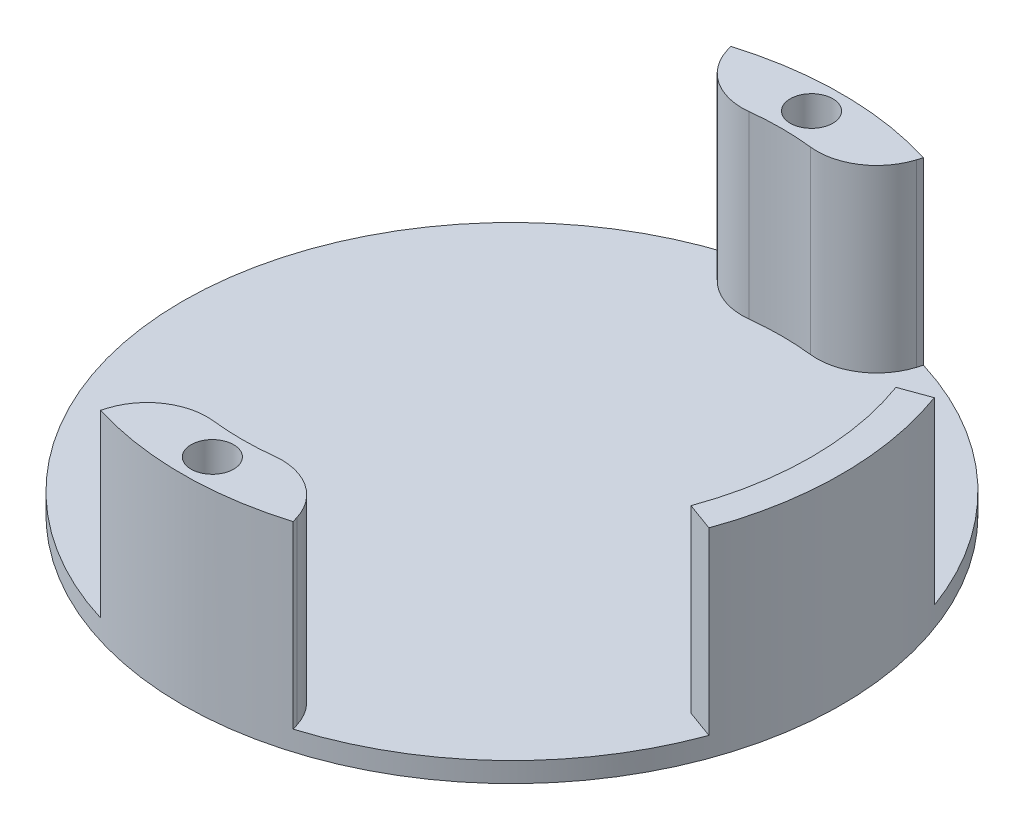
SolidWorks part; units mm, degrees
ref_plane "Front Plane" through (0, 0, 0) normal (0, 0, 1) x (1, 0, 0)
ref_plane "Top Plane" through (0, 0, 0) normal (0, 1, 0) x (1, 0, 0)
ref_plane "Right Plane" through (0, 0, 0) normal (1, 0, 0) x (0, 0, -1)
sketch "Sketch2" plane through (0, 0, 0) normal (0, 1, 0) x (1, 0, 0)
  circle A0 centre (0, 0) radius 69.85
  dimension "D1" = 139.7
extrude "Boss-Extrude1" add sketch "Sketch2" along normal blind 4.2333
sketch "Sketch3" plane through (0, 4.2333, 0) normal (0, 1, 0) x (1, 0, 0)
  line L0 (-20.4222, 66.7979) -> (-16.709, 54.6528)
  line L5 (20.4222, 66.7979) -> (16.709, 54.6528)
  line L6 (16.709, -54.6528) -> (20.4222, -66.7979)
  line L7 (-16.709, -54.6528) -> (-20.4222, -66.7979)
  arc A6 (20.4222, 66.7979) -> (-20.4222, 66.7979) centre (0, 0) ccw
  arc A7 (-16.709, -54.6528) -> (16.709, -54.6528) centre (0, 0) ccw
  arc A8 (-20.4222, -66.7979) -> (20.4222, -66.7979) centre (0, 0) ccw
  arc A9 (16.709, 54.6528) -> (-16.709, 54.6528) centre (0, 0) ccw
  circle M3 centre (0, 0) radius 69.85
  dimension "D1" = 114.3
extrude "Boss-Extrude2" add sketch "Sketch3" along normal blind 38.1 contours A7 L7 L6 M3 | A9 L5 L0 M3
fillet "Fillet3" radius 12.7 1 edges at (-16.709, 23.2833, -54.6528)
fillet "Fillet4" radius 12.7 1 edges at (16.709, 23.2833, 54.6528)
fillet "Fillet5" radius 12.7 1 edges at (-16.709, 23.2833, 54.6528)
sketch "Sketch4" plane through (0, 4.2333, 0) normal (0, 1, 0) x (1, 0, 0)
  line L0 (59.6705, 21.7183) -> (65.6375, 23.8901)
  line L1 (59.6705, -21.7183) -> (65.6375, -23.8901)
  arc A0 (65.6375, -23.8901) -> (65.6375, 23.8901) centre (0, 0) ccw
  arc A1 (59.6705, -21.7183) -> (59.6705, 21.7183) centre (0, 0) ccw
  dimension "D1" = 127
extrude "Boss-Extrude3" add sketch "Sketch4" along normal blind 38.1
sketch "Sketch5" plane through (0, 42.3333, 0) normal (0, 1, 0) x (1, 0, 0)
  circle A0 centre (0, 63.5) radius 4.5085
  circle A1 centre (0, -63.5) radius 4.5085
  arc A3 (-20.4222, -66.7979) -> (20.4222, -66.7979) centre (0, 0) ccw construction
  point P7 (0, -69.85)
  dimension "D1" = 9.017
  dimension "D2" = 9.017
  dimension "D3" = 127
  dimension "D4" = 6.35
extrude "Cut-Extrude1" cut sketch "Sketch5" against normal through all both and the other way through all
fillet "Fillet6" radius 12.7 1 edges at (16.709, 23.2833, -54.6528)
